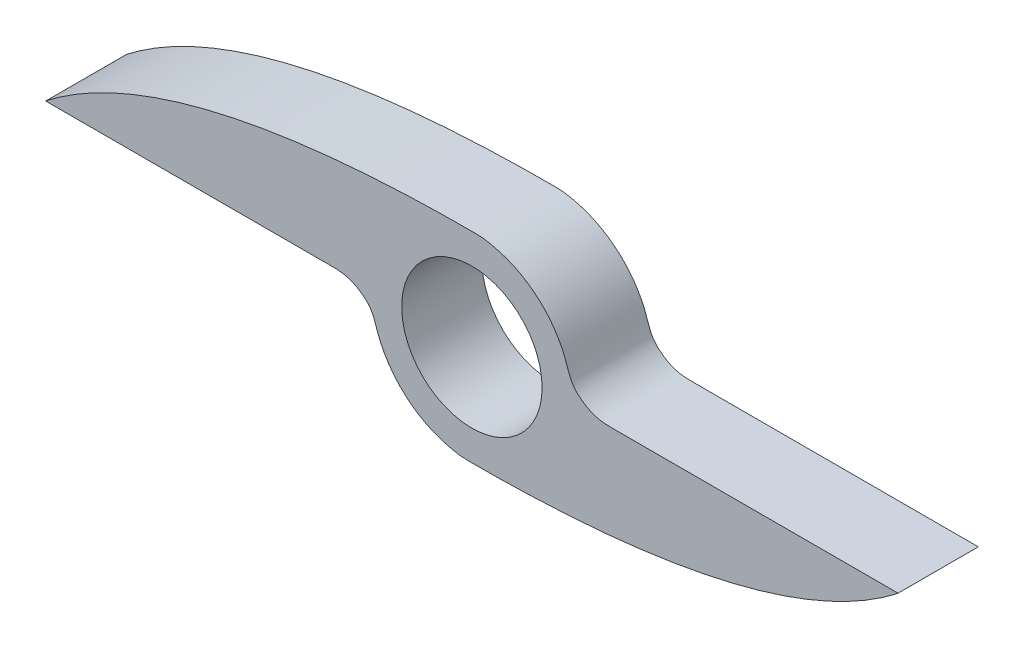
SolidWorks part; units mm, degrees
ref_plane "Front Plane" through (0, 0, 0) normal (0, 0, 1) x (1, 0, 0)
ref_plane "Top Plane" through (0, 0, 0) normal (0, 1, 0) x (1, 0, 0)
ref_plane "Right Plane" through (0, 0, 0) normal (1, 0, 0) x (0, 0, -1)
sketch "Sketch1" plane through (0, 0, 0) normal (0, 0, 1) x (1, 0, 0)
  line L0 (0, 0) -> (14.1421, 0) construction
  circle A6 centre (0, 0) radius 7
  spline S0 degree 3 poles (14.1421, 0) (23.5571, 0) (32.9721, 0) (42.3871, 0) (42.3953, 0) (42.4117, 0) (42.4687, -0.0246) (42.4558, -0.0347) (42.4493, -0.0398) (42.4437, -0.0442) (42.4324, -0.053) (42.4155, -0.0663) (42.4042, -0.0751) (42.3986, -0.0795) (34.39, -6.3256) (21.3393, -9.6222) (3.2463, -9.9694) (2.868, -9.9766) (2.1113, -9.9885) (0.9761, -9.9983) (0.2193, -9.9995) (-0.1591, -9.9987) (-0.4822, -9.9981) (-1.1284, -9.9949) (-2.0958, -9.794) (-2.7211, -9.6281) (-3.0291, -9.5302) (-6.0711, -8.5633) (-8.3641, -6.3428) (-9.4281, -3.3333) (-9.6419, -2.7285) (-9.9532, -1.4777) (-12.2176, 0) (-13.5006, 0) (-14.1421, 0) (-23.5571, 0) (-32.9721, 0) (-42.3871, 0) (-42.3953, 0) (-42.4117, 0) (-42.4687, 0.0246) (-42.4558, 0.0347) (-42.4493, 0.0398) (-42.4437, 0.0442) (-42.4324, 0.053) (-42.4155, 0.0663) (-42.4042, 0.0751) (-42.3986, 0.0795) (-34.39, 6.3256) (-21.3393, 9.6222) (-3.2463, 9.9694) (-2.868, 9.9766) (-2.1113, 9.9885) (-0.9761, 9.9983) (-0.2193, 9.9995) (0.1591, 9.9987) (0.4822, 9.9981) (1.1284, 9.9949) (2.0958, 9.794) (2.7211, 9.6281) (3.0291, 9.5302) (6.0711, 8.5633) (8.3641, 6.3428) (9.4281, 3.3333) (9.6419, 2.7285) (9.9532, 1.4777) (12.2176, 0) (13.5006, 0) (14.1421, 0) (23.5571, 0) (32.9721, 0) knots -0.005497 0 0 0 0.256123 0.256123 0.256123 0.256346 0.25657 0.256793 0.256793 0.256793 0.256988 0.257182 0.257377 0.257377 0.257377 0.533668 0.533668 0.533668 0.539445 0.545223 0.551 0.551 0.551 0.555933 0.560866 0.565799 0.565799 0.565799 0.611133 0.611133 0.611133 0.620928 0.630722 0.640516 0.640516 0.640516 0.784263 0.784263 0.784263 0.784388 0.784514 0.784639 0.784639 0.784639 0.784748 0.784857 0.784967 0.784967 0.784967 0.940032 0.940032 0.940032 0.943275 0.946517 0.94976 0.94976 0.94976 0.952528 0.955297 0.958066 0.958066 0.958066 0.983509 0.983509 0.983509 0.989006 0.994503 1 1 1 1.256123 1.256123 1.256123 weights 1 1 1 1 1 1 1 1 1 1 1 1 1 1 1 1 1 1 1 1 1 1 1 1 1 1 1 0.930224 0.930224 1 1 1 1 1 1 1 1 1 1 1 1 1 1 1 1 1 1 1 1 1 1 1 1 1 1 1 1 1 1 1 1 0.930224 0.930224 1 1 1 1 1 1 1 1 only from (14.1421, 0) to (14.1421, 0)
extrude "Boss-Extrude1" add sketch "Sketch1" along normal blind 8
ref_plane "Plane1" through (0, 0, 4) normal (0, 0, 1) x (1, 0, 0)
sketch "Sketch2" plane through (0, 0, 4) normal (0, 0, 1) x (1, 0, 0)
  spline S0 degree 3 poles (14.1421, 0) (23.5571, 0) (32.9721, 0) (42.3871, 0) (42.3953, 0) (42.4117, 0) (42.4687, -0.0246) (42.4558, -0.0347) (42.4493, -0.0398) (42.4437, -0.0442) (42.4324, -0.053) (42.4155, -0.0663) (42.4042, -0.0751) (42.3986, -0.0795) (34.39, -6.3256) (21.3393, -9.6222) (3.2463, -9.9694) (2.868, -9.9766) (2.1113, -9.9885) (0.9761, -9.9983) (0.2193, -9.9995) (-0.1591, -9.9987) (-0.4822, -9.9981) (-1.1284, -9.9949) (-2.0958, -9.794) (-2.7211, -9.6281) (-3.0291, -9.5302) (-6.0711, -8.5633) (-8.3641, -6.3428) (-9.4281, -3.3333) (-9.6419, -2.7285) (-9.9532, -1.4777) (-12.2176, 0) (-13.5006, 0) (-14.1421, 0) (-23.5571, 0) (-32.9721, 0) (-42.3871, 0) (-42.3953, 0) (-42.4117, 0) (-42.4687, 0.0246) (-42.4558, 0.0347) (-42.4493, 0.0398) (-42.4437, 0.0442) (-42.4324, 0.053) (-42.4155, 0.0663) (-42.4042, 0.0751) (-42.3986, 0.0795) (-34.39, 6.3256) (-21.3393, 9.6222) (-3.2463, 9.9694) (-2.868, 9.9766) (-2.1113, 9.9885) (-0.9761, 9.9983) (-0.2193, 9.9995) (0.1591, 9.9987) (0.4822, 9.9981) (1.1284, 9.9949) (2.0958, 9.794) (2.7211, 9.6281) (3.0291, 9.5302) (6.0711, 8.5633) (8.3641, 6.3428) (9.4281, 3.3333) (9.6419, 2.7285) (9.9532, 1.4777) (12.2176, 0) (13.5006, 0) (14.1421, 0) (23.5571, 0) (32.9721, 0) knots -0.005497 0 0 0 0.256123 0.256123 0.256123 0.256346 0.25657 0.256793 0.256793 0.256793 0.256988 0.257182 0.257377 0.257377 0.257377 0.533668 0.533668 0.533668 0.539445 0.545223 0.551 0.551 0.551 0.555933 0.560866 0.565799 0.565799 0.565799 0.611133 0.611133 0.611133 0.620928 0.630722 0.640516 0.640516 0.640516 0.784263 0.784263 0.784263 0.784388 0.784514 0.784639 0.784639 0.784639 0.784748 0.784857 0.784967 0.784967 0.784967 0.940032 0.940032 0.940032 0.943275 0.946517 0.94976 0.94976 0.94976 0.952528 0.955297 0.958066 0.958066 0.958066 0.983509 0.983509 0.983509 0.989006 0.994503 1 1 1 1.256123 1.256123 1.256123 weights 1 1 1 1 1 1 1 1 1 1 1 1 1 1 1 1 1 1 1 1 1 1 1 1 1 1 1 0.930224 0.930224 1 1 1 1 1 1 1 1 1 1 1 1 1 1 1 1 1 1 1 1 1 1 1 1 1 1 1 1 1 1 1 1 0.930224 0.930224 1 1 1 1 1 1 1 1 only from (14.1421, 0) to (14.1421, 0)
